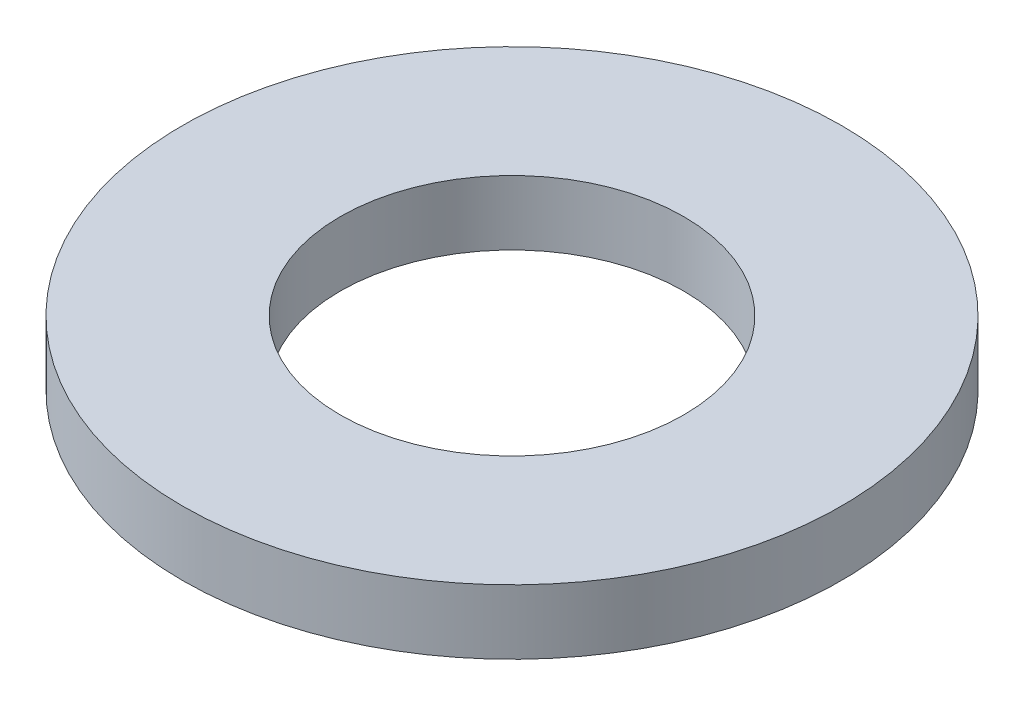
SolidWorks part; units mm, degrees
material "Delrin 2700 NC010, Low Viscosity Acetal Copolymer (SS)"
ref_plane "Front Plane" through (0, 0, 0) normal (0, 0, 1) x (1, 0, 0)
ref_plane "Top Plane" through (0, 0, 0) normal (0, 1, 0) x (1, 0, 0)
ref_plane "Right Plane" through (0, 0, 0) normal (1, 0, 0) x (0, 0, -1)
sketch "Sketch1" plane through (0, 0, 0) normal (0, 1, 0) x (-1, 0, 0)
  circle A0 centre (-19.4582, -21.0585) radius 32.75
  circle A2 centre (-19.4582, -21.0585) radius 62.833
extrude "Boss-Extrude1" add sketch "Sketch1" along normal blind 12.3
